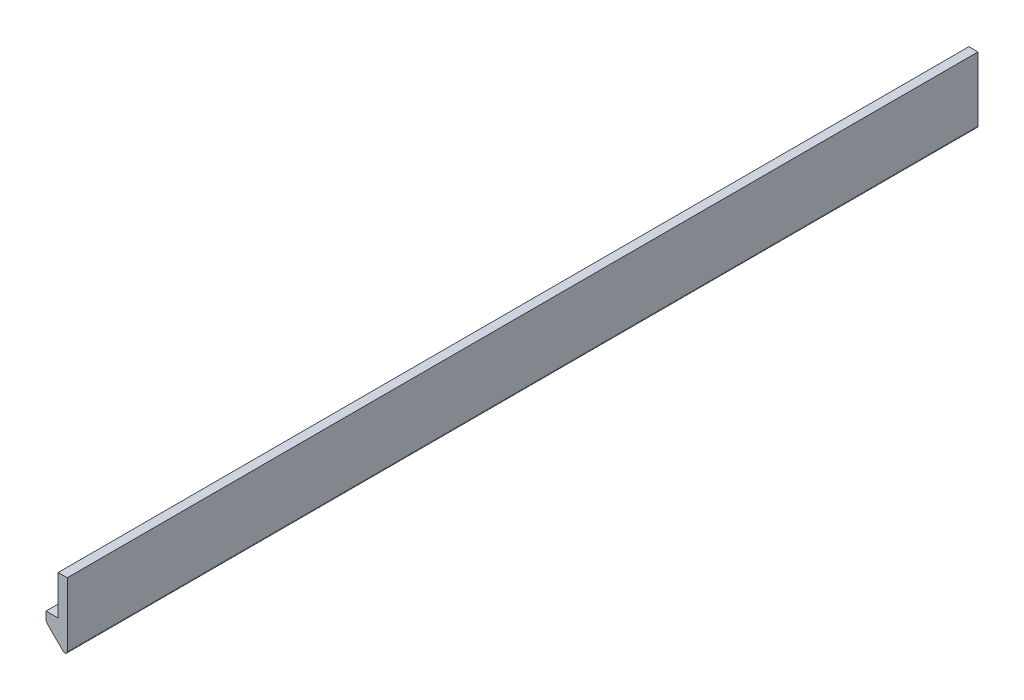
SolidWorks part; units mm, degrees
ref_plane "Front Plane" through (0, 0, 0) normal (0, 0, 1) x (1, 0, 0)
ref_plane "Top Plane" through (0, 0, 0) normal (0, 1, 0) x (1, 0, 0)
ref_plane "Right Plane" through (0, 0, 0) normal (1, 0, 0) x (0, 0, -1)
ref_plane "Plane1" through (0, 0, 280) normal (0, 0, 1) x (1, 0, 0)
sketch "Sketch1" plane through (0, 0, 280) normal (0, 0, 1) x (1, 0, 0)
  line L0 (-7, 4) -> (4, -7)
  line L1 (4, -7) -> (7, -7)
  line L2 (7, -7) -> (7, -3)
  line L3 (7, -3) -> (20, -3)
  line L4 (20, -3) -> (20, 0)
  line L5 (20, 0) -> (0, 0)
  line L6 (0, 0) -> (0, 20)
  line L7 (0, 20) -> (-3, 20)
  line L8 (-3, 20) -> (-3, 7)
  line L9 (-3, 7) -> (-7, 7)
  line L10 (-7, 7) -> (-7, 4)
extrude "Boss-Extrude1" add sketch "Sketch1" against normal blind 300
fillet "Fillet1" radius 1.5 2 edges at (-7, 4, 130) (4, -7, 130)
sketch "Sketch2" plane through (0, 0, 0) normal (0, 1, 0) x (1, 0, 0)
  line L4 (0, -280) -> (20, -280)
  line L5 (20, -280) -> (20, 20)
  line L6 (20, 20) -> (0, 20)
  line L7 (0, 20) -> (0, -280)
  line L8 (0, -280) -> (20, -280)
  line L9 (20, -280) -> (20, 20)
  line L10 (20, 20) -> (0, 20)
  line L11 (0, 20) -> (0, -280)
  dimension "D1" = 0
extrude "Cut-Extrude1" cut sketch "Sketch2" against normal blind 10
fillet "Fillet2" radius 0.8 1 edges at (0, -3, 130)
